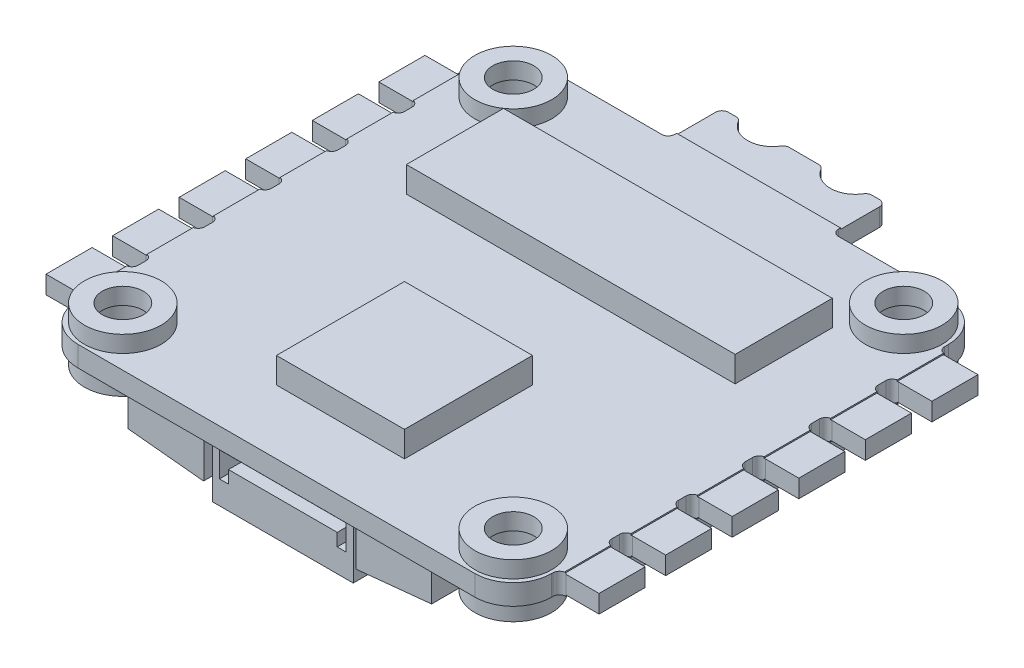
SolidWorks part; units mm, degrees
ref_plane "前视基准面" through (0, 0, 0) normal (0, 0, 1) x (1, 0, 0)
ref_plane "上视基准面" through (0, 0, 0) normal (0, 1, 0) x (1, 0, 0)
ref_plane "右视基准面" through (0, 0, 0) normal (1, 0, 0) x (0, 0, -1)
sketch "草图1" plane through (0, 0, 0) normal (0, 1, 0) x (1, 0, 0)
  line L1 (-18.5, -18.5) -> (18.5, -18.5)
  line L2 (-18.5, -18.5) -> (-18.5, 18.5)
  line L3 (-18.5, 18.5) -> (18.5, 18.5)
  line L4 (18.5, -18.5) -> (18.5, 18.5)
  line L5 (-18.5, -18.5) -> (18.5, 18.5) construction
  line L6 (-18.5, 18.5) -> (18.5, -18.5) construction
  line L7 (-15.25, -15.25) -> (15.25, -15.25)
  line L8 (-15.25, -15.25) -> (-15.25, 15.25)
  line L9 (-15.25, 15.25) -> (15.25, 15.25)
  line L10 (15.25, -15.25) -> (15.25, 15.25)
  line L11 (-15.25, -15.25) -> (15.25, 15.25) construction
  line L12 (-15.25, 15.25) -> (15.25, -15.25) construction
  circle A0 centre (15.25, 15.25) radius 2.25
  circle A1 centre (15.25, -15.25) radius 2.25
  circle A2 centre (-15.25, -15.25) radius 2.25
  circle A3 centre (-15.25, 15.25) radius 2.25
  point P0 (0, 0)
  point P6 (0, 0)
  point P21 (0, 0)
  dimension "D4" = 4.5
  dimension "D1" = 37
  dimension "D2" = 37
  dimension "D3" = 30.5
  dimension "D5" = 4
extrude "凸台-拉伸1" add sketch "草图1" along normal blind 1.6 contours L1 L4 L3 L2 A3 L9 A0 L10 A1 L7 A2 L8 | A3 L8 A2 L7 A1 L10 A0 L9
fillet "圆角1" radius 3 4 edges at (18.5, 0.8, -18.5) (18.5, 0.8, 18.5) (-18.5, 0.8, 18.5) (-18.5, 0.8, -18.5)
sketch "草图2" plane through (0, 0, 0) normal (0, -1, 0) x (1, 0, 0)
  circle A0 centre (-15.25, 15.25) radius 3
  circle A1 centre (-15.25, 15.25) radius 1.6
  circle A2 centre (15.25, 15.25) radius 1.6
  circle A3 centre (15.25, 15.25) radius 3
  circle A4 centre (15.25, -15.25) radius 1.6
  circle A5 centre (15.25, -15.25) radius 3
  circle A6 centre (-15.25, -15.25) radius 1.6
  circle A7 centre (-15.25, -15.25) radius 3
  point P16 (0, 0)
  dimension "D1" = 3.2
  dimension "D3" = 6
  dimension "D2" = 4
extrude "凸台-拉伸2" add sketch "草图2" along normal blind 1.3 separate body
sketch "草图3" plane through (0, 1.6, 0) normal (0, 1, 0) x (1, 0, 0)
  circle A0 centre (-15.25, 15.25) radius 3
  circle A1 centre (-15.25, 15.25) radius 1.6
  circle A2 centre (15.25, 15.25) radius 1.6
  circle A3 centre (15.25, 15.25) radius 3
  circle A4 centre (15.25, -15.25) radius 1.6
  circle A5 centre (15.25, -15.25) radius 3
  circle A6 centre (-15.25, -15.25) radius 1.6
  circle A7 centre (-15.25, -15.25) radius 3
  point P16 (0, 0)
  dimension "D1" = 6
  dimension "D2" = 4
extrude "凸台-拉伸3" add sketch "草图3" along normal blind 1.3 separate body
sketch "草图6" plane through (0, 0, 0) normal (0, -1, 0) x (1, 0, 0)
  line L0 (0, 0) -> (0, 18.5) construction
  line L1 (-15.5, 18.5) -> (15.5, 18.5) construction
  line L3 (-5.5, 18) -> (5.5, 18)
  line L4 (-5.5, 18) -> (-5.5, 13.7)
  line L5 (-5.5, 13.7) -> (5.5, 13.7)
  line L6 (5.5, 18) -> (5.5, 13.7)
  line L7 (-5.5, 18) -> (5.5, 13.7) construction
  line L8 (-5.5, 13.7) -> (5.5, 18) construction
  point P5 (0, 15.85)
  dimension "D1" = 11
  dimension "D2" = 4.3
  dimension "D3" = 0.5
extrude "凸台-拉伸5" add sketch "草图6" along normal blind 4.3 separate body
sketch "草图7" plane through (0, 0, 18) normal (0, 0, 1) x (1, 0, 0)
  line L0 (0, 0) -> (0, -4.3) construction
  line L1 (5.5, -4.3) -> (-5.5, -4.3) construction
  line L2 (4.9505, -0.5083) -> (-4.9505, -0.5083)
  line L3 (-4.9505, -0.5083) -> (-4.9505, -2.4796)
  line L4 (-4.9505, -2.4796) -> (-4.2473, -2.4796)
  line L5 (-4.2473, -2.4796) -> (-4.2473, -1.494)
  line L6 (-4.2473, -1.494) -> (4.2473, -1.494)
  line L7 (4.2473, -2.4796) -> (4.2473, -1.494)
  line L8 (4.9505, -2.4796) -> (4.2473, -2.4796)
  line L9 (4.9505, -0.5083) -> (4.9505, -2.4796)
  point P12 (0, -1.494)
  point P15 (0, -0.5083)
extrude "切除-拉伸2" cut sketch "草图7" against normal blind 3.3
sketch "草图9" plane through (0, 1.6, 0) normal (0, 1, 0) x (1, 0, 0)
  line L0 (0, 0) -> (0, -18.5) construction
  line L1 (-15.5, -18.5) -> (15.5, -18.5) construction
  line L3 (-5, -13.5) -> (5, -13.5)
  line L4 (-5, -13.5) -> (-5, -3.5)
  line L5 (-5, -3.5) -> (5, -3.5)
  line L6 (5, -13.5) -> (5, -3.5)
  line L7 (-5, -13.5) -> (5, -3.5) construction
  line L8 (-5, -3.5) -> (5, -13.5) construction
  line L9 (-12.8405, 12.0771) -> (12.8405, 12.0771)
  line L10 (-12.8405, 12.0771) -> (-12.8405, 4.4891)
  line L11 (-12.8405, 4.4891) -> (12.8405, 4.4891)
  line L12 (12.8405, 12.0771) -> (12.8405, 4.4891)
  line L13 (-12.8405, 12.0771) -> (12.8405, 4.4891) construction
  line L14 (-12.8405, 4.4891) -> (12.8405, 12.0771) construction
  point P5 (0, -8.5)
  point P10 (0, 8.2831)
  dimension "D1" = 10
  dimension "D2" = 10
  dimension "D3" = 5
extrude "凸台-拉伸7" add sketch "草图9" along normal blind 2 separate body
sketch "草图10" plane through (0, 0, 0) normal (0, -1, 0) x (1, 0, 0)
  line L0 (0, -18.5) -> (0, 18.617) construction
  line L1 (-15.5, -18.5) -> (15.5, -18.5) construction
  line L2 (5.9474, 13.2393) -> (-5.9474, 13.2393)
  line L3 (-5.9474, 13.2393) -> (-5.9474, 18.2297)
  line L4 (-5.9474, 18.2297) -> (-11.8493, 18.2297)
  line L5 (-11.8493, 18.2297) -> (-11.8493, 11.8948)
  line L6 (-11.8493, 11.8948) -> (-18.1613, 11.8948)
  line L7 (-18.1613, 11.8948) -> (-18.1613, -11.8721)
  line L8 (-18.1613, -11.8721) -> (-11.8721, -11.8721)
  line L9 (-11.8721, -11.8721) -> (-11.8721, -17.9334)
  line L10 (-11.8721, -17.9334) -> (-5.674, -17.9334)
  line L11 (-5.674, -17.9334) -> (-4.1472, -16.9308)
  line L12 (-4.1472, -16.9308) -> (4.1472, -16.9308)
  line L13 (5.674, -17.9334) -> (4.1472, -16.9308)
  line L14 (11.8721, -17.9334) -> (5.674, -17.9334)
  line L15 (11.8721, -11.8721) -> (11.8721, -17.9334)
  line L16 (18.1613, -11.8721) -> (11.8721, -11.8721)
  line L17 (18.1613, 11.8948) -> (18.1613, -11.8721)
  line L18 (11.8493, 11.8948) -> (18.1613, 11.8948)
  line L19 (11.8493, 18.2297) -> (11.8493, 11.8948)
  line L20 (5.9474, 18.2297) -> (11.8493, 18.2297)
  line L21 (5.9474, 13.2393) -> (5.9474, 18.2297)
  point P18 (0, -16.9308)
  point P27 (0, 13.2393)
extrude "凸台-拉伸8" add sketch "草图10" along normal blind 3 separate body
sketch "草图11" plane through (0, 0, 0) normal (0, 0, 1) x (1, 0, 0)
  line L0 (18.1613, -1.7939) -> (6.1276, -3)
  line L1 (18.1613, -3) -> (18.1613, 0) construction
  line L2 (5.674, -3) -> (11.8721, -3) construction
  line L3 (6.1276, -3) -> (18.1613, -3)
  line L4 (18.1613, -3) -> (18.1613, -1.7939)
  line L5 (0, 0) -> (0, -3) construction
  line L6 (-4.1472, -3) -> (4.1472, -3) construction
  line L7 (-18.1613, -3) -> (-18.1613, -1.7939)
  line L8 (-6.1276, -3) -> (-18.1613, -3)
  line L9 (-18.1613, -1.7939) -> (-6.1276, -3)
extrude "切除-拉伸3" cut sketch "草图11" against normal through all both and the other way through all
sketch "草图12" plane through (0, 0, 0) normal (0, -1, 0) x (1, 0, 0)
  line L0 (18.5, 15.5) -> (18.5, -15.5) construction
  line L1 (18.5, 14.9) -> (21.6, 14.9)
  line L2 (18.5, 14.9) -> (18.5, 11.3)
  line L3 (18.5, 11.3) -> (21.6, 11.3)
  line L4 (21.6, 14.9) -> (21.6, 11.3)
  line L5 (-15.5, 18.5) -> (15.5, 18.5) construction
  line L6 (18.5, 9.7) -> (18.5, 6.1)
  line L7 (18.5, 9.7) -> (21.6, 9.7)
  line L8 (21.6, 9.7) -> (21.6, 6.1)
  line L9 (18.5, 6.1) -> (21.6, 6.1)
  line L10 (18.5, 4.5) -> (18.5, 0.9)
  line L11 (18.5, 4.5) -> (21.6, 4.5)
  line L12 (21.6, 4.5) -> (21.6, 0.9)
  line L13 (18.5, 0.9) -> (21.6, 0.9)
  line L14 (18.5, -0.7) -> (18.5, -4.3)
  line L15 (18.5, -0.7) -> (21.6, -0.7)
  line L16 (21.6, -0.7) -> (21.6, -4.3)
  line L17 (18.5, -4.3) -> (21.6, -4.3)
  line L18 (18.5, -5.9) -> (18.5, -9.5)
  line L19 (18.5, -5.9) -> (21.6, -5.9)
  line L20 (21.6, -5.9) -> (21.6, -9.5)
  line L21 (18.5, -9.5) -> (21.6, -9.5)
  line L22 (18.5, -11.1) -> (18.5, -14.7)
  line L23 (18.5, -11.1) -> (21.6, -11.1)
  line L24 (21.6, -11.1) -> (21.6, -14.7)
  line L25 (18.5, -14.7) -> (21.6, -14.7)
  line L26 (0, 0) -> (0, 27.3925) construction
  line L27 (-18.5, -14.7) -> (-21.6, -14.7)
  line L28 (-21.6, -11.1) -> (-21.6, -14.7)
  line L29 (-18.5, -11.1) -> (-21.6, -11.1)
  line L30 (-18.5, -11.1) -> (-18.5, -14.7)
  line L31 (-18.5, -9.5) -> (-21.6, -9.5)
  line L32 (-21.6, -5.9) -> (-21.6, -9.5)
  line L33 (-18.5, -5.9) -> (-21.6, -5.9)
  line L34 (-18.5, -5.9) -> (-18.5, -9.5)
  line L35 (-18.5, -4.3) -> (-21.6, -4.3)
  line L36 (-21.6, -0.7) -> (-21.6, -4.3)
  line L37 (-18.5, -0.7) -> (-21.6, -0.7)
  line L38 (-18.5, -0.7) -> (-18.5, -4.3)
  line L39 (-18.5, 0.9) -> (-21.6, 0.9)
  line L40 (-21.6, 4.5) -> (-21.6, 0.9)
  line L41 (-18.5, 4.5) -> (-21.6, 4.5)
  line L42 (-18.5, 4.5) -> (-18.5, 0.9)
  line L43 (-18.5, 6.1) -> (-21.6, 6.1)
  line L44 (-21.6, 9.7) -> (-21.6, 6.1)
  line L45 (-18.5, 9.7) -> (-21.6, 9.7)
  line L46 (-18.5, 9.7) -> (-18.5, 6.1)
  line L47 (-21.6, 14.9) -> (-21.6, 11.3)
  line L48 (-18.5, 11.3) -> (-21.6, 11.3)
  line L49 (-18.5, 14.9) -> (-18.5, 11.3)
  line L50 (-18.5, 14.9) -> (-21.6, 14.9)
  dimension "D1" = 3.1
  dimension "D2" = 3.6
  dimension "D3" = 3.6
  dimension "D4" = 6
extrude "凸台-拉伸9" add sketch "草图12" against normal up to surface (1.6 mm away) up to face at (15.25, 1.6, -13)
fillet "圆角2" radius 0.5 24 edges at (-18.5, 0.8, -11.1) (-18.5, 0.8, -5.9) (-18.5, 0.8, -0.7) (-18.5, 0.8, 4.5) (-18.5, 0.8, 9.7) (-18.5, 0.8, 14.9) (-18.5, 0.8, 11.3) (-18.5, 0.8, 6.1) (-18.5, 0.8, 0.9) (-18.5, 0.8, -4.3) (-18.5, 0.8, -9.5) (-18.5, 0.8, -14.7) (18.5, 0.8, 6.1) (18.5, 0.8, 0.9) (18.5, 0.8, -14.7) (18.5, 0.8, -4.3) (18.5, 0.8, -9.5) (18.5, 0.8, -11.1) (18.5, 0.8, -5.9) (18.5, 0.8, -0.7) (18.5, 0.8, 4.5) (18.5, 0.8, 9.7) (18.5, 0.8, 11.3) (18.5, 0.8, 14.9)
sketch "草图13" plane through (0, 0, 0) normal (0, -1, 0) x (1, 0, 0)
  line L0 (19, -14.7) -> (21.6, -14.7) construction
  line L1 (21.6, 14.9) -> (18.9, 14.9)
  line L2 (21.6, 14.9) -> (21.6, -14.7)
  line L3 (21.6, -14.7) -> (18.9, -14.7)
  line L4 (18.9, 14.9) -> (18.9, -14.7)
  line L5 (0, 0) -> (0, 18.5) construction
  line L6 (-15.5, 18.5) -> (15.5, 18.5) construction
  line L7 (-21.6, -14.7) -> (-18.9, -14.7)
  line L8 (-18.9, 14.9) -> (-18.9, -14.7)
  line L9 (-21.6, 14.9) -> (-18.9, 14.9)
  line L10 (-21.6, 14.9) -> (-21.6, -14.7)
  dimension "D1" = 2.7
extrude "切除-拉伸4" cut sketch "草图13" against normal blind 0.1
sketch "草图14" plane through (0, 1.6, 0) normal (0, 1, 0) x (1, 0, 0)
  line L0 (-19, -14.9) -> (-21.6, -14.9) construction
  line L1 (-21.6, 14.7) -> (-18.9, 14.7)
  line L2 (-21.6, 14.7) -> (-21.6, -14.9)
  line L3 (-21.6, -14.9) -> (-18.9, -14.9)
  line L4 (-18.9, 14.7) -> (-18.9, -14.9)
  line L5 (0, 0) -> (0, 18.5) construction
  line L6 (-15.5, 18.5) -> (15.5, 18.5) construction
  line L7 (21.6, -14.9) -> (18.9, -14.9)
  line L8 (18.9, 14.7) -> (18.9, -14.9)
  line L9 (21.6, 14.7) -> (18.9, 14.7)
  line L10 (21.6, 14.7) -> (21.6, -14.9)
  dimension "D1" = 2.7
extrude "切除-拉伸5" cut sketch "草图14" against normal blind 0.1
sketch "草图15" plane through (0, 0, 0) normal (0, -1, 0) x (1, 0, 0)
  line L0 (0, -18.5) -> (0, -24.5698) construction
  line L1 (-15.5, -18.5) -> (15.5, -18.5) construction
  line L2 (6.4, -18.5) -> (-6.4, -18.5)
  line L3 (-6.4, -18.5) -> (-6.4, -22.7)
  line L4 (-6.4, -22.7) -> (-5.0152, -22.7)
  line L5 (-1.4433, -22.7) -> (1.4433, -22.7)
  line L6 (6.4, -22.7) -> (5.0152, -22.7)
  line L7 (6.4, -18.5) -> (6.4, -22.7)
  arc A0 (-5.0152, -22.7) -> (-1.4433, -22.7) centre (-3.2293, -23.4877) cw
  arc A1 (5.0152, -22.7) -> (1.4433, -22.7) centre (3.2293, -23.4877) ccw
  point P11 (0, -22.7)
  dimension "D1" = 6.4
  dimension "D2" = 4.2
extrude "凸台-拉伸10" add sketch "草图15" against normal up to surface (1.6 mm away) up to face at (0, 1.6, 0.0867)
fillet "圆角3" radius 0.5 8 edges at (-6.4, 0.8, -22.7) (-5.0152, 0.8, -22.7) (-1.4433, 0.8, -22.7) (1.4433, 0.8, -22.7) (5.0152, 0.8, -22.7) (6.4, 0.8, -22.7) (6.4, 0.8, -18.5) (-6.4, 0.8, -18.5)
sketch "草图16" plane through (0, 0, 0) normal (0, -1, 0) x (1, 0, 0)
  line L0 (-6.4, -19) -> (-6.4, -22.2) construction
  line L1 (-6.4, -19.1796) -> (6.4, -19.1796)
  line L2 (-6.4, -19.1796) -> (-6.4, -23.077)
  line L3 (-6.4, -23.077) -> (6.4, -23.077)
  line L4 (6.4, -19.1796) -> (6.4, -23.077)
  line L5 (6.4, -22.2) -> (6.4, -19) construction
extrude "切除-拉伸6" cut sketch "草图16" against normal blind 0.1
sketch "草图17" plane through (0, 1.6, 0) normal (0, 1, 0) x (1, 0, 0)
  line L0 (-6.4, 19) -> (-6.4, 22.2) construction
  line L1 (-6.4, 19.1586) -> (6.4, 19.1586)
  line L2 (-6.4, 19.1586) -> (-6.4, 23.3059)
  line L3 (-6.4, 23.3059) -> (6.4, 23.3059)
  line L4 (6.4, 19.1586) -> (6.4, 23.3059)
  line L5 (6.4, 22.2) -> (6.4, 19) construction
extrude "切除-拉伸7" cut sketch "草图17" against normal blind 0.1
